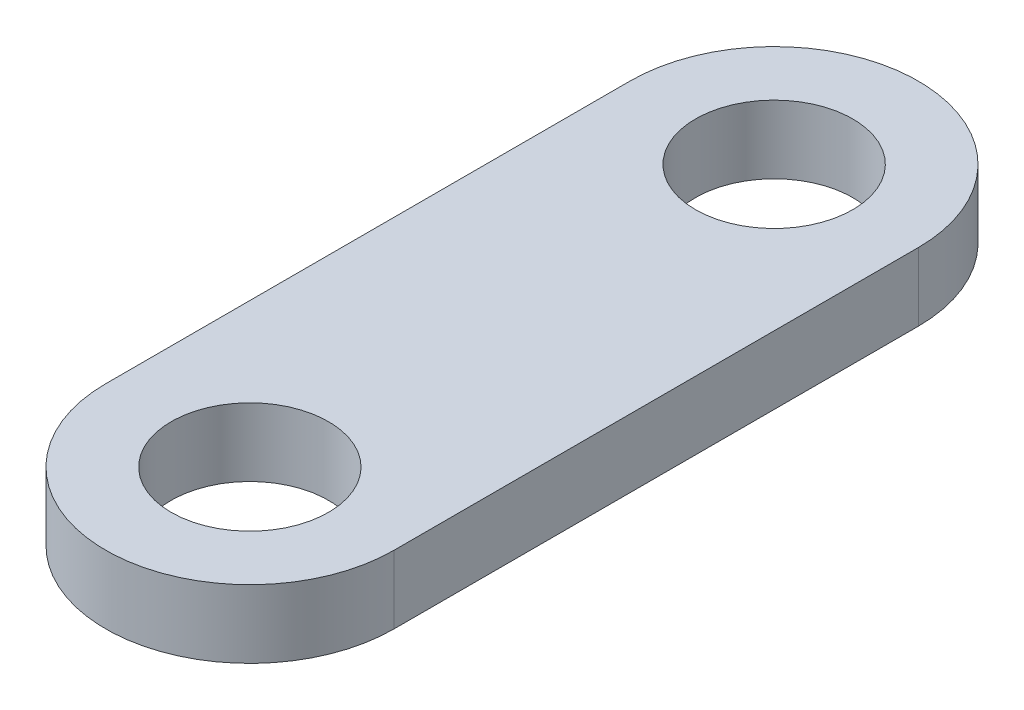
SolidWorks part; units mm, degrees
ref_plane "Front Plane" through (0, 0, 0) normal (0, 0, 1) x (1, 0, 0)
ref_plane "Top Plane" through (0, 0, 0) normal (0, 1, 0) x (1, 0, 0)
ref_plane "Right Plane" through (0, 0, 0) normal (1, 0, 0) x (0, 0, -1)
sketch "Sketch1" plane through (0, 0, 0) normal (0, 1, 0) x (1, 0, 0)
  line L0 (0, 12.3977) -> (0, -7.6023) construction
  line L1 (5.5, 12.3977) -> (5.5, -7.6023)
  line L2 (-5.5, 12.3977) -> (-5.5, -7.6023)
  arc A0 (5.5, 12.3977) -> (-5.5, 12.3977) centre (0, 12.3977) ccw
  arc A1 (-5.5, -7.6023) -> (5.5, -7.6023) centre (0, -7.6023) ccw
  circle A2 centre (0, 12.3977) radius 3
  circle A3 centre (0, -7.6023) radius 3
  point P3 (0, 2.3977)
  dimension "D1" = 5.5
  dimension "D3" = 6
  dimension "D4" = 6
  dimension "D2" = 20
extrude "Boss-Extrude1" add sketch "Sketch1" along normal blind 2.6
